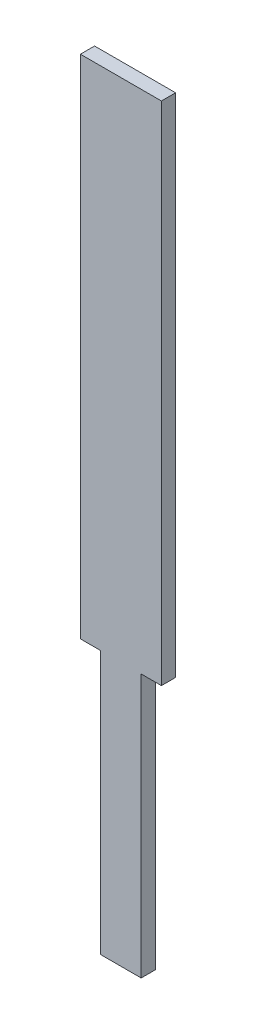
SolidWorks part; units mm, degrees
ref_plane "Front Plane" through (0, 0, 0) normal (0, 0, 1) x (1, 0, 0)
ref_plane "Top Plane" through (0, 0, 0) normal (0, 1, 0) x (1, 0, 0)
ref_plane "Right Plane" through (0, 0, 0) normal (1, 0, 0) x (0, 0, -1)
sketch "Sketch1" plane through (0, 0, 0) normal (0, 0, 1) x (1, 0, 0)
  line L1 (-20, -125) -> (20, -125)
  line L2 (-20, -125) -> (-20, 125)
  line L3 (-20, 125) -> (20, 125)
  line L4 (20, -125) -> (20, 125)
  line L5 (-20, -125) -> (20, 125) construction
  line L6 (-20, 125) -> (20, -125) construction
  line L7 (-10, -125) -> (10, -125)
  line L8 (-10, -125) -> (-10, -255)
  line L9 (-10, -255) -> (10, -255)
  line L10 (10, -125) -> (10, -255)
  point P0 (0, 0)
  dimension "D1" = 130
  dimension "D2" = 40
  dimension "D3" = 250
  dimension "D4" = 10
  dimension "D5" = 10
extrude "Boss-Extrude1" add sketch "Sketch1" along normal blind 7 contours L1 L4 L3 L2 | L10 L1 L8 L9
